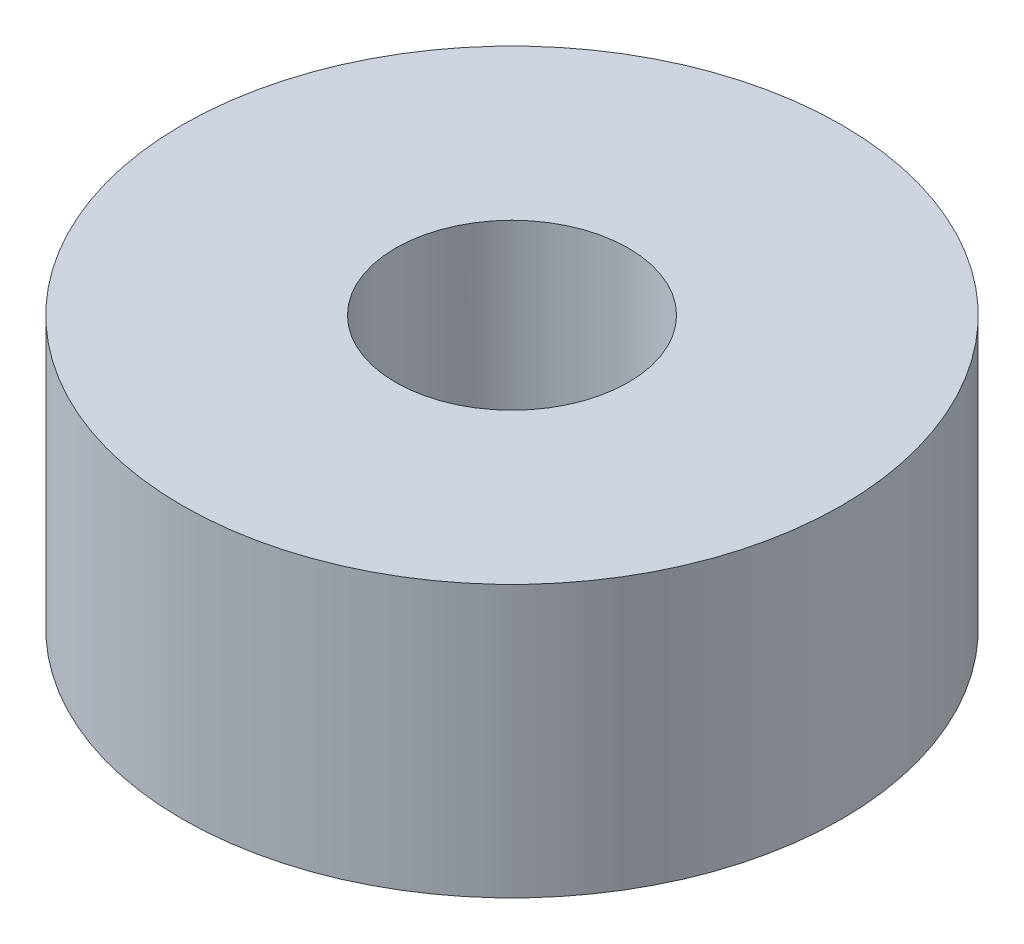
SolidWorks part; units mm, degrees
ref_plane "Front Plane" through (0, 0, 0) normal (0, 0, 1) x (1, 0, 0)
ref_plane "Top Plane" through (0, 0, 0) normal (0, 1, 0) x (1, 0, 0)
ref_plane "Right Plane" through (0, 0, 0) normal (1, 0, 0) x (0, 0, -1)
sketch "Sketch1" plane through (0, 0, 0) normal (0, 1, 0) x (1, 0, 0)
  circle A0 centre (0, 0) radius 8.5
  dimension "D1" = 17
extrude "Boss-Extrude1" add sketch "Sketch1" along normal blind 7
sketch "Sketch2" plane through (0, 0, 0) normal (0, -1, 0) x (1, 0, 0)
  circle A0 centre (0, 0) radius 3
  dimension "D1" = 6
extrude "Cut-Extrude1" cut sketch "Sketch2" against normal blind 10
